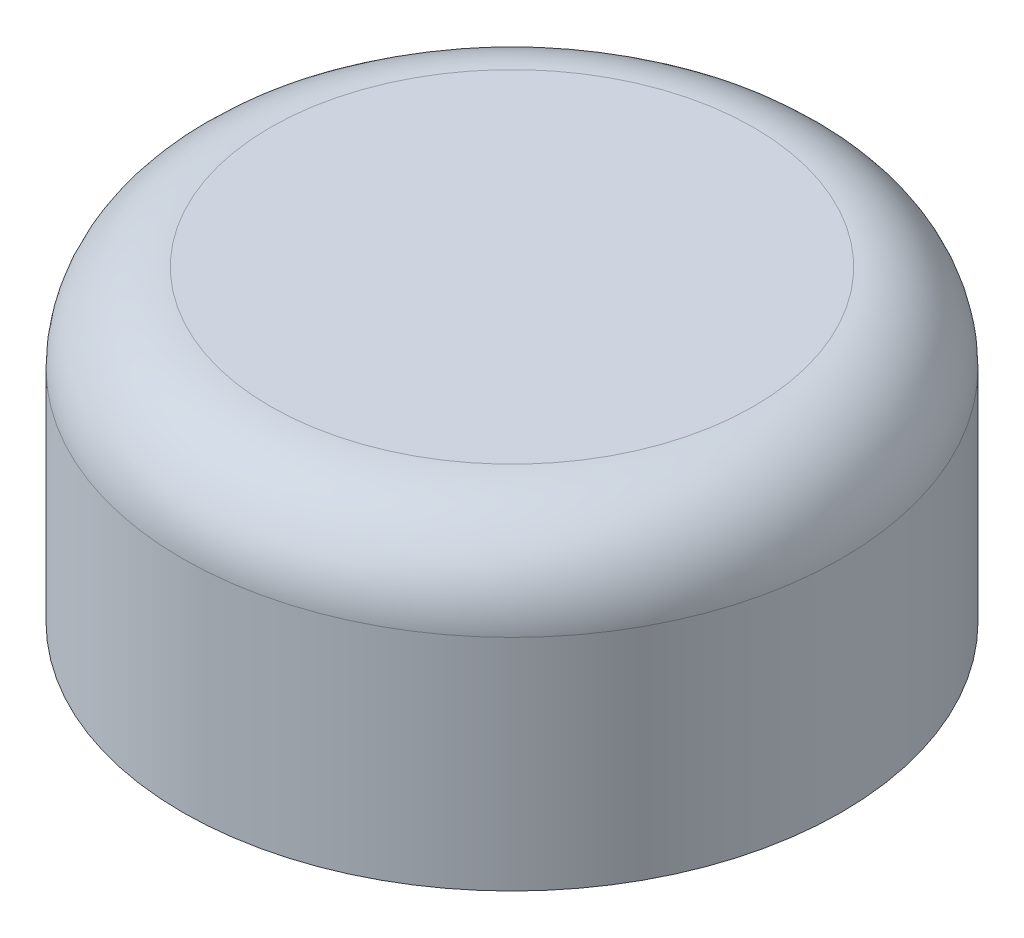
SolidWorks part; units mm, degrees
material "99.5% Aluminum Oxide"
ref_plane "Front Plane" through (0, 0, 0) normal (0, 0, 1) x (1, 0, 0)
ref_plane "Top Plane" through (0, 0, 0) normal (0, 1, 0) x (1, 0, 0)
ref_plane "Right Plane" through (0, 0, 0) normal (1, 0, 0) x (0, 0, -1)
sketch "Sketch1" plane through (0, 0, 0) normal (0, 1, 0) x (1, 0, 0)
  circle A0 centre (0, 0) radius 37.5
  dimension "D1" = 75
extrude "Boss-Extrude1" add sketch "Sketch1" along normal mid plane 35
fillet "Fillet1" radius 10 1 edges at (0, 17.5, 37.5)
